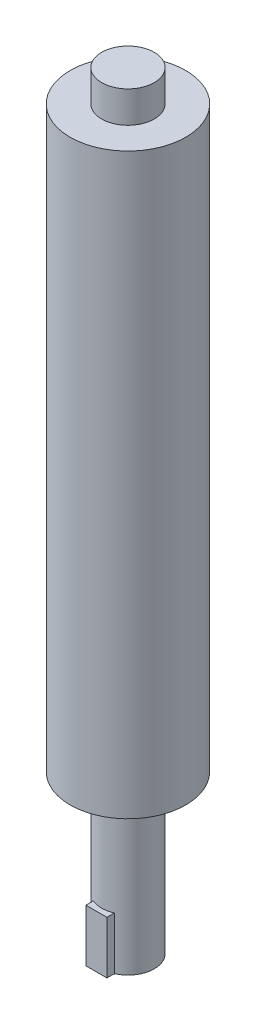
SolidWorks part; units mm, degrees
ref_plane "前视基准面" through (0, 0, 0) normal (0, 0, 1) x (1, 0, 0)
ref_plane "上视基准面" through (0, 0, 0) normal (0, 1, 0) x (1, 0, 0)
ref_plane "右视基准面" through (0, 0, 0) normal (1, 0, 0) x (0, 0, -1)
other "Configuration Table"
sketch "草图1" plane through (0, 0, 0) normal (0, 1, 0) x (1, 0, 0)
  circle A0 centre (0, 0) radius 2.5
  dimension "D1" = 5
extrude "凸台-拉伸1" add sketch "草图1" along normal mid plane 61
sketch "草图2" plane through (0, 0, 0) normal (0, 1, 0) x (1, 0, 0)
  circle A0 centre (0, 0) radius 5.5
  dimension "D1" = 11
extrude "凸台-拉伸2" add sketch "草图2" along normal mid plane 55
sketch "草图3" plane through (0, -30.5, 0) normal (0, -1, 0) x (1, 0, 0)
  circle A1 centre (0, 0) radius 2.5
  circle A2 centre (0, 0) radius 2.5
  dimension "D1" = 0
extrude "凸台-拉伸3" add sketch "草图3" along normal blind 12
sketch "草图4" plane through (0, -42.5, 0) normal (0, -1, 0) x (1, 0, 0)
  line L1 (-1, 3) -> (1, 3)
  line L2 (-1, 3) -> (-1, 2)
  line L3 (-1, 2) -> (1, 2)
  line L4 (1, 3) -> (1, 2)
  line L5 (-1, 3) -> (1, 2) construction
  line L6 (-1, 2) -> (1, 3) construction
  circle A0 centre (0, 0) radius 2.5 construction
  circle A1 centre (0, 0) radius 2.5 construction
  point P0 (0, 2.5)
  dimension "D1" = 2
  dimension "D2" = 1
extrude "凸台-拉伸4" add sketch "草图4" against normal blind 5
hole_wizard "M4 螺纹孔1" positions "草图5" profile "草图6" tap size "M4" standard "GB"
sketch "草图5" plane through (0, -42.5, 0) normal (0, -1, 0) x (-1, 0, 0)
  point P0 (0, 0)
sketch "草图6" plane through (0, -42.5, 0) normal (1, 0, 0) x (0, 0, -1)
  line L0 (0, 0) -> (0, 11.5)
  line L1 (0, 11.5) -> (1.65, 10.5086)
  line L2 (1.65, 10.5086) -> (1.65, 0)
  line L5 (1.65, 0) -> (0, 0)
  line L10 (0, 11.5) -> (-1.65, 10.5086) construction
  line L11 (0, -6.35) -> (0, 107.95) construction
  dimension "螺纹孔钻头直径" = 3.3
  dimension "螺纹孔钻头深度" = 11.5
  dimension "导头角度" = 118
cosmetic thread "孔螺纹线1" parameters "D1"=8, "D2"=4
